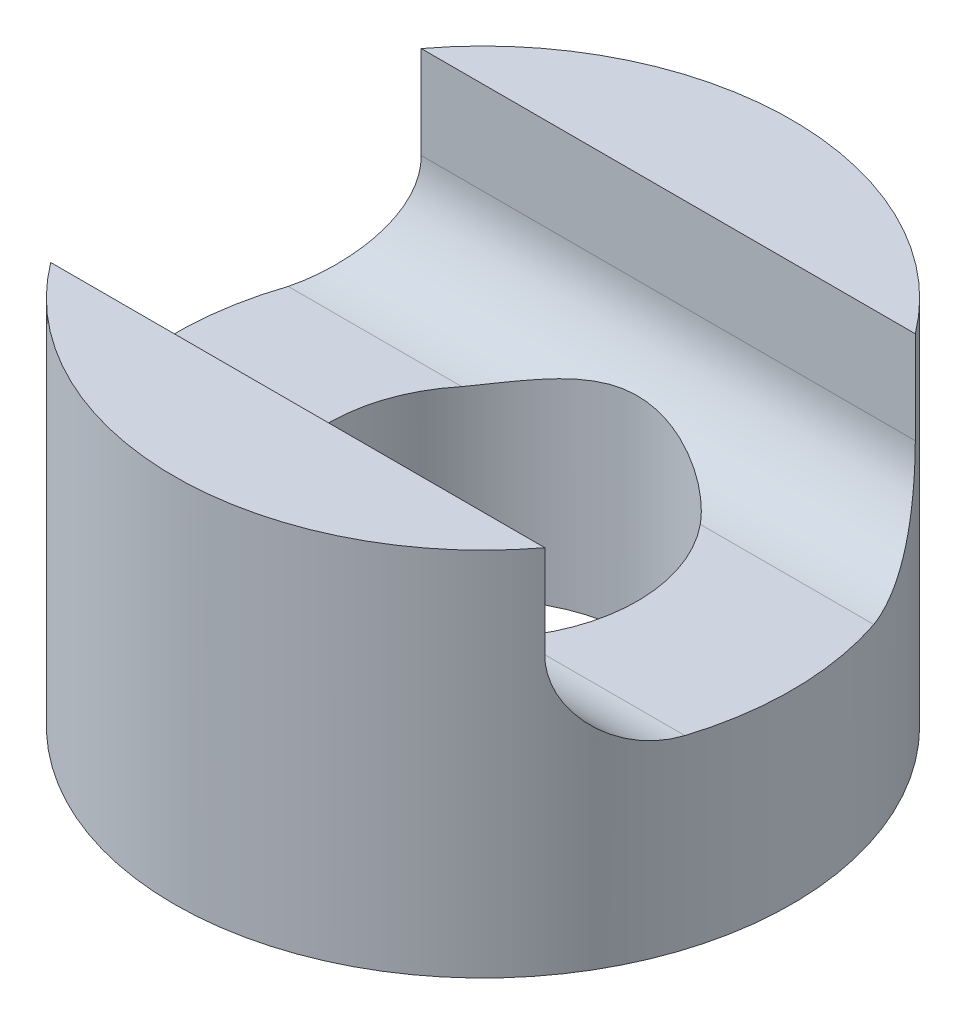
SolidWorks part; units mm, degrees
ref_plane "Front Plane" through (0, 0, 0) normal (0, 0, 1) x (1, 0, 0)
ref_plane "Top Plane" through (0, 0, 0) normal (0, 1, 0) x (1, 0, 0)
ref_plane "Right Plane" through (0, 0, 0) normal (1, 0, 0) x (0, 0, -1)
sketch "Sketch1" plane through (0, 0, 0) normal (0, 1, 0) x (1, 0, 0)
  circle A0 centre (0, 0) radius 3.9688
  circle A1 centre (0, 0) radius 7.9375
  dimension "D1" = 7.9375
  dimension "D2" = 15.875
extrude "Boss-Extrude1" add sketch "Sketch1" along normal blind 9.525
sketch "Sketch2" plane through (0, 0, 0) normal (1, 0, 0) x (0, 0, -1)
  line L0 (7.9375, 9.525) -> (-7.9375, 9.525) construction
  line L1 (-4.7625, 9.525) -> (4.7625, 9.525)
  line L2 (-4.7625, 9.525) -> (-4.7625, 7.1437)
  line L3 (-2.3812, 4.7625) -> (2.5194, 4.7625)
  line L4 (4.7625, 9.525) -> (4.7625, 7.1438)
  arc A0 (-4.7625, 7.1437) -> (-2.3812, 4.7625) centre (-2.3812, 7.1438) ccw
  arc A1 (4.7625, 7.1438) -> (2.5194, 4.7625) centre (2.377, 7.1438) cw
  point P14 (-2.79, 7.1437)
  point P15 (0, 0)
  point P16 (0, 0)
  dimension "D4" = 2.3855
  dimension "D1" = 9.525
  dimension "D2" = 4.9007
  dimension "D3" = 2.3812
extrude "Cut-Extrude1" cut sketch "Sketch2" against normal through all and the other way through all
